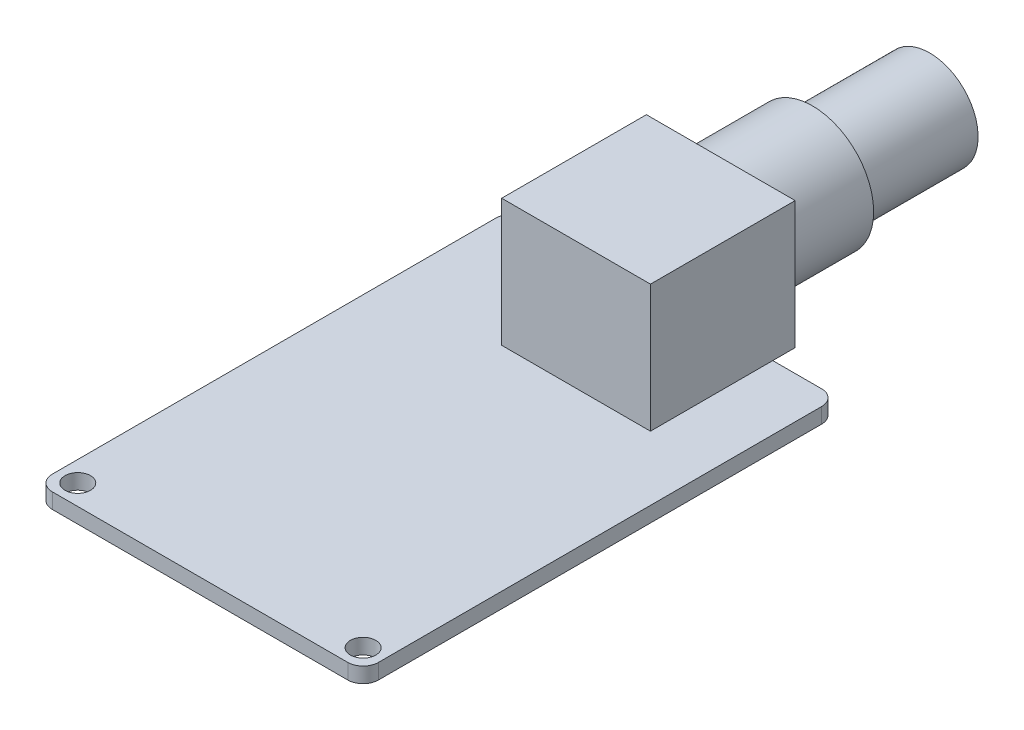
SolidWorks part; units mm, degrees
ref_plane "前基準面" through (0, 0, 0) normal (0, 0, 1) x (1, 0, 0)
ref_plane "上基準面" through (0, 0, 0) normal (0, 1, 0) x (1, 0, 0)
ref_plane "右基準面" through (0, 0, 0) normal (1, 0, 0) x (0, 0, -1)
sketch "草圖1" plane through (0, 0, 0) normal (0, 0, 1) x (1, 0, 0)
  line L0 (-101.7064, 41) -> (-14.1064, 41) construction
  line L2 (-12.0331, 2) -> (-12.0331, 43) construction
  circle A0 centre (-29.3409, 31.5) radius 6
  dimension "D1" = 12
  dimension "D3" = 17.3078
  dimension "D2" = 9.5
extrude "填料-伸長1" add sketch "草圖1" against normal blind 5.5 and the other way blind 3.5
sketch "草圖2" plane through (0, 0, -5.5) normal (0, 0, -1) x (-1, 0, 0)
  circle A0 centre (29.3409, 31.5) radius 4.75
  circle A1 centre (29.3409, 31.5) radius 6 construction
  dimension "D1" = 0
extrude "填料-伸長2" add sketch "草圖2" along normal blind 11.5
sketch "草圖3" plane through (0, 0, -17) normal (0, 0, -1) x (-1, 0, 0)
  circle A2 centre (29.3409, 31.5) radius 4.25
  circle A3 centre (29.3409, 31.5) radius 4.25
  dimension "D1" = 0.5
extrude "除料-伸長1" cut sketch "草圖3" against normal blind 11.5
sketch "草圖4" plane through (0, 0, 3.5) normal (0, 0, 1) x (1, 0, 0)
  line L1 (-36.6409, 37.6) -> (-22.0409, 37.6)
  line L2 (-36.6409, 37.6) -> (-36.6409, 25.1)
  line L3 (-36.6409, 25.1) -> (-22.0409, 25.1)
  line L4 (-22.0409, 37.6) -> (-22.0409, 25.1)
  circle A1 centre (-29.3409, 31.5) radius 6 construction
  point P6 (-22.0409, 31.35)
  dimension "D1" = 7.3
  dimension "D2" = 6.1
  dimension "D3" = 14.6
extrude "填料-伸長3" add sketch "草圖4" along normal blind 14.2
sketch "草圖5" plane through (0, 25.1, 0) normal (0, -1, 0) x (1, 0, 0)
  line L0 (-22.0409, 17.7) -> (-22.0409, 3.5) construction
  line L1 (-17.2409, 5.6974) -> (-46.2409, 5.6974)
  line L2 (-15.7409, 7.1974) -> (-15.7409, 50.6974)
  line L3 (-17.2409, 52.1974) -> (-46.2409, 52.1974)
  line L4 (-47.7409, 7.1974) -> (-47.7409, 50.6974)
  arc A0 (-15.7409, 50.6974) -> (-17.2409, 52.1974) centre (-17.2409, 50.6974) ccw
  arc A1 (-46.2409, 52.1974) -> (-47.7409, 50.6974) centre (-46.2409, 50.6974) ccw
  arc A2 (-46.2409, 5.6974) -> (-47.7409, 7.1974) centre (-46.2409, 7.1974) cw
  arc A3 (-17.2409, 5.6974) -> (-15.7409, 7.1974) centre (-17.2409, 7.1974) ccw
  circle A4 centre (-17.7409, 50.1974) radius 1.25
  circle A5 centre (-45.7409, 50.1974) radius 1.25
  point P8 (-15.7409, 52.1974)
  point P11 (-47.7409, 52.1974)
  point P14 (-47.7409, 5.6974)
  dimension "D4" = 1.5
  dimension "D5" = 2.5
  dimension "D6" = 2.5
  dimension "D7" = 2
  dimension "D8" = 2
  dimension "D9" = 2
  dimension "D10" = 2
  dimension "D1" = 32
  dimension "D2" = 46.5
  dimension "D3" = 6.3
extrude "填料-伸長4" add sketch "草圖5" along normal blind 1.5
